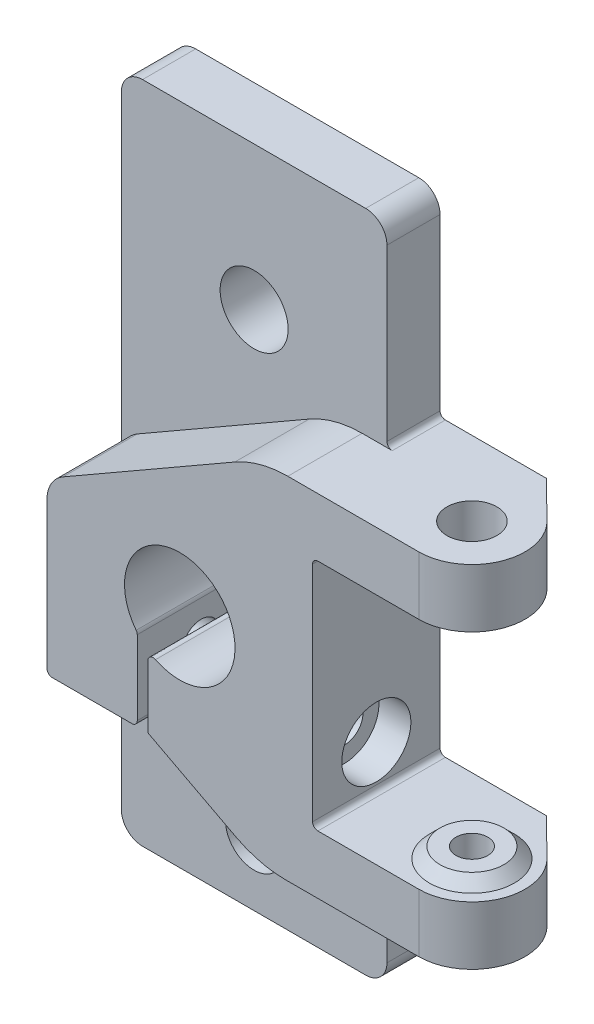
SolidWorks part; units mm, degrees
ref_plane "XY" through (0, 0, 0) normal (0, 0, 1) x (1, 0, 0)
ref_plane "XZ" through (0, 0, 0) normal (0, 1, 0) x (1, 0, 0)
ref_plane "YZ" through (0, 0, 0) normal (1, 0, 0) x (0, 0, -1)
sketch "Sketch1" plane through (0, 0, 0) normal (0, 0, 1) x (1, 0, 0)
  line L0 (5, 31.25) -> (5, -31.25)
  line L1 (20, 31.25) -> (5, 31.25) construction
  line L2 (20, 31.25) -> (20, -31.25) construction
  line L3 (20, -31.25) -> (5, -31.25) construction
  line L4 (-20, 31.25) -> (-20, -31.25)
  line L5 (20, 31.25) -> (-20, -31.25) construction
  line L6 (20, -31.25) -> (-20, 31.25) construction
  line L7 (5, 31.25) -> (-20, 31.25)
  line L8 (5, -31.25) -> (-20, -31.25)
  line L9 (-7.5, 31.25) -> (-7.5, -43.6532) construction
  line L10 (-20, -14.75) -> (-11.5, -14.75)
  line L11 (-11.5, -14.75) -> (-11.5, -7.0726)
  line L12 (-20, -15.75) -> (-10.5, -15.75)
  line L13 (-10.5, -15.75) -> (-10.5, -7.9974)
  line L14 (-10.5, -15.75) -> (-10.5, -7.0726) construction
  circle A0 centre (-7.5, 17.75) radius 3.2
  arc A1 (-10.5, -7.9974) -> (-11.5, -7.0726) centre (-7.5, -3.75) ccw
  circle A2 centre (-7.5, -25.25) radius 2.7
  point P0 (0, 0)
  dimension "D4" = 6.4
  dimension "D5" = 10.4
  dimension "D6" = 5.4
  dimension "D1" = 40
  dimension "D2" = 62.5
  dimension "D3" = 25
  dimension "D7" = 13.5
  dimension "D8" = 21.5
  dimension "D9" = 21.5
  dimension "D10" = 1
  dimension "D11" = 8.5
  dimension "D12" = 16.5
extrude "Boss-Extrude1" add sketch "Sketch1" along normal blind 5 contours A1 L13 L12 L4 L8 L0 L7 L10 L11 A2 A0
ref_plane "Plane1" through (0, 0, 12) normal (0, 0, 1) x (1, 0, 0)
sketch "Sketch2" plane through (0, 0, 12) normal (0, 0, 1) x (1, 0, 0)
  line L0 (0, 12.75) -> (20, 12.75)
  line L1 (20, -31.25) -> (-20, -31.25) construction
  line L2 (20, -31.25) -> (20, 31.25) construction
  line L3 (20, 31.25) -> (-20, 31.25) construction
  line L4 (-20, -31.25) -> (-20, 31.25) construction
  line L5 (20, -31.25) -> (-20, 31.25) construction
  line L6 (20, 31.25) -> (-20, -31.25) construction
  line L7 (20, 12.75) -> (20, 7.25)
  line L8 (20, 7.25) -> (5, 7.25)
  line L9 (-10.5, -7.9974) -> (-10.5, -15.75)
  line L10 (-10.5, -15.75) -> (-20, -15.75)
  line L11 (-20, -15.75) -> (-20, -31.25)
  line L12 (-20, -31.25) -> (5, -31.25)
  line L13 (5, -31.25) -> (5, 31.25)
  line L14 (5, 31.25) -> (-20, 31.25)
  line L15 (-20, 31.25) -> (-20, -14.75)
  line L16 (-20, -14.75) -> (-11.5, -14.75)
  line L17 (-11.5, -14.75) -> (-11.5, -7.0726)
  line L18 (-10.5, -7.9974) -> (-10.5, -14.75)
  line L19 (-10.5, -15.75) -> (-20, -15.75) construction
  line L20 (-7.5, -3.75) -> (38.2201, -3.75) construction
  line L21 (20, -14.75) -> (5, -14.75)
  line L22 (20, -20.25) -> (20, -14.75)
  line L23 (0, -20.25) -> (20, -20.25)
  line L24 (5, 31.25) -> (5, -31.25) construction
  line L25 (-20, -14.75) -> (-11.5, -14.75)
  line L26 (-11.5, -14.75) -> (-11.5, -7.0726)
  line L27 (5, 7.25) -> (5, -14.75)
  line L28 (0, 12.75) -> (-20, 1.25)
  line L29 (-20, 1.25) -> (-20, -14.75)
  line L30 (0, -20.25) -> (-10.5, -14.75)
  line L31 (-10.5, -14.75) -> (-10.5, -15.75) construction
  arc A1 (-10.5, -7.9974) -> (-11.5, -7.0726) centre (-7.5, -3.75) ccw
  arc A2 (-10.5, -7.9974) -> (-11.5, -7.0726) centre (-7.5, -3.75) ccw
  point P0 (0, 0)
  dimension "D2" = 18.5
  dimension "D3" = 5.5
  dimension "D4" = 20
  dimension "D5" = 30
  dimension "D1" = 0
extrude "Boss-Extrude2" add sketch "Sketch2" against normal up to surface (12 mm away) up to face at (-4.8, -25.25, 0)
sketch "Sketch3" plane through (0, -20.25, 0) normal (0, -1, 0) x (1, 0, 0)
  line L0 (15, 0) -> (20, 0)
  line L1 (20, 0) -> (5, 0) construction
  line L2 (20, 0) -> (20, 4.9)
  line L3 (20, 0) -> (20, 12) construction
  line L4 (20, 4.9) -> (15, 0)
  line L5 (15, 0) -> (15.0489, 0.0293)
  circle A0 centre (15, 7) radius 1.5
  dimension "D3" = 3
  dimension "D1" = 5
  dimension "D2" = 4.9
  dimension "D4" = 7
extrude "Cut-Extrude1" cut sketch "Sketch3" against normal through all
fillet "Fillet1" radius 4.9995 4 edges at (20, 10, 12) (20, 7.25, 8.45) (20, 12.75, 8.45) (20, 10, 4.9)
fillet "Fillet2" radius 4.9995 4 edges at (20, -17.5, 12) (20, -20.25, 8.45) (20, -14.75, 8.45) (20, -17.5, 4.9)
sketch "Sketch4" plane through (0, 7.25, 0) normal (0, -1, 0) x (1, 0, 0)
  circle A0 centre (15, 7) radius 3
  dimension "D1" = 6
extrude "Boss-Extrude3" add sketch "Sketch4" along normal blind 1
draft "Draft1" type of draft neutral plane draft angle 45 faces to draft 1 face at (18, 6.25, 7) neutral plane through (15, 6.25, 7) neutral plane normal (0, -1, 0) parameters "D1"=45
ref_plane "Plane2" through (0, -3.75, 0) normal (0, 1, 0) x (1, 0, 0)
mirror "Mirror1" about plane through (0, -3.75, 0) normal (0, 1, 0) of "Draft1", "Boss-Extrude3"
sketch "Sketch5" plane through (0, -20.25, 0) normal (0, -1, 0) x (1, 0, 0)
  circle A0 centre (15, 7) radius 1.5 construction
  circle A1 centre (15, 7) radius 1.5
extrude "Cut-Extrude2" cut sketch "Sketch5" against normal through all
sketch "Sketch6" plane through (0, -20.25, 0) normal (0, -1, 0) x (1, 0, 0)
  circle A0 centre (15, 7) radius 3.1
  dimension "D1" = 6.2
extrude "Cut-Extrude3" cut sketch "Sketch6" against normal blind 1.5
mirror "Mirror2" about plane through (0, -3.75, 0) normal (0, 1, 0) of "Cut-Extrude3"
fillet "Fillet3" radius 10 2 edges at (0, -20.25, 8.5) (0, 12.75, 8.5)
fillet "Fillet5" radius 0.5 9 edges at (-11.5, -7.0726, 6) (-11.5, -14.75, 6) (-20, -14.75, 6) (-20, -15.75, 2.5) (-10.5, -7.9974, 6) (5, 7.25, 6) (5, 12.75, 2.5) (5, -14.75, 6) (5, -20.25, 2.5)
fillet "Fillet6" radius 2 4 edges at (-20, 31.25, 2.5) (5, 31.25, 2.5) (5, -31.25, 2.5) (-20, -31.25, 2.5)
fillet "Fillet7" radius 3 1 edges at (-20, 1.25, 8.5)
ref_plane "Plane3" through (0, 0, 6) normal (0, 0, 1) x (1, 0, 0)
sketch "Sketch7" plane through (0, 0, 6) normal (0, 0, 1) x (1, 0, 0)
  line L0 (-28.8022, -10.75) -> (15.2765, -10.75) construction
  line L1 (5, -10.75) -> (5, -7.5)
  line L2 (5, -14.25) -> (5, 6.75) construction
  line L3 (5, -7.5) -> (2, -7.5)
  line L4 (2, -7.5) -> (2, -9)
  line L5 (2, -9) -> (-15, -9)
  line L8 (-20, -10.75) -> (5, -10.75)
  line L12 (-15, -9) -> (-15, -8.4)
  line L13 (-15, -8.4) -> (-19, -8.4)
  line L14 (-19, -8.4) -> (-19, -8.25)
  line L15 (-19, -8.25) -> (-20, -8.25)
  line L16 (-20, -0.4856) -> (-20, -14.25) construction
  line L17 (-20, -8.25) -> (-20, -10.75)
  dimension "D1" = 10.75
  dimension "D2" = 3.25
  dimension "D3" = 1.75
  dimension "D4" = 3
  dimension "D5" = 2.5
  dimension "D6" = 1
  dimension "D7" = 2.35
  dimension "D8" = 4
revolve "Cut-Revolve3" cut sketch "Sketch7" angle 360 about L0
sketch "Sketch8" plane through (0, 12.75, 0) normal (0, 1, 0) x (1, 0, 0)
  circle A0 centre (15, -7) radius 3.1
  circle A1 centre (15, -7) radius 2.35
  dimension "D1" = 4.7
  dimension "D2" = 6.2
extrude "Boss-Extrude4" add sketch "Sketch8" against normal up to surface (1.5 mm away) up to face at (15, 11.25, 3.9)
sketch "Sketch9" plane through (0, 11.25, 0) normal (0, 1, 0) x (1, 0, 0)
  circle A0 centre (15, -7) radius 2.35 construction
  circle A1 centre (15, -7) radius 2.35
  circle A2 centre (15, -7) radius 1.5
extrude "Cut-Extrude4" cut sketch "Sketch9" against normal blind 4
